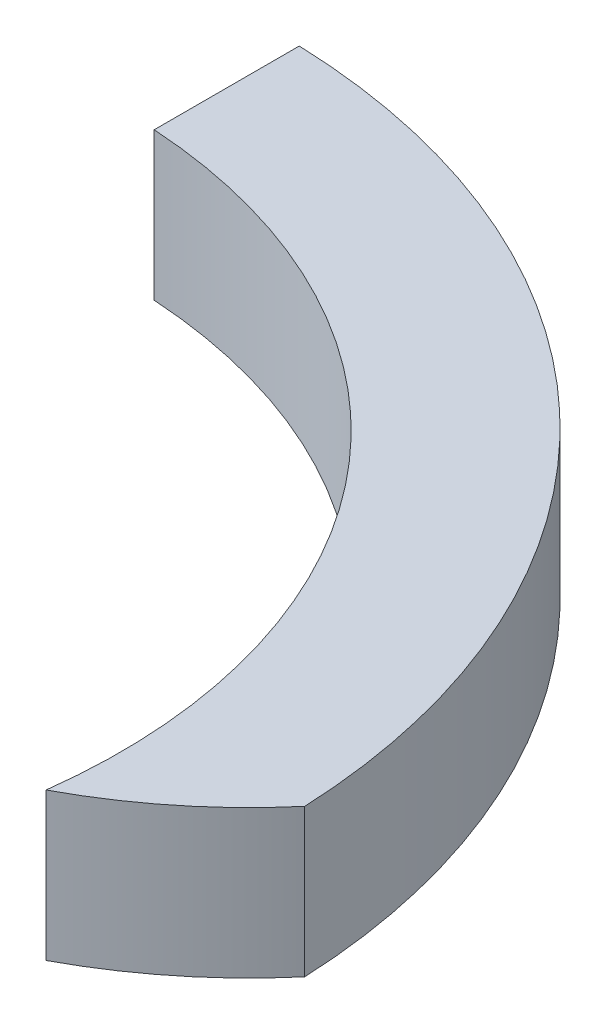
SolidWorks part; units mm, degrees
ref_plane "Front Plane" through (0, 0, 0) normal (0, 0, 1) x (1, 0, 0)
ref_plane "Top Plane" through (0, 0, 0) normal (0, 1, 0) x (1, 0, 0)
ref_plane "Right Plane" through (0, 0, 0) normal (1, 0, 0) x (0, 0, -1)
sketch "Sketch1" plane through (0, 0, 0) normal (0, 1, 0) x (1, 0, 0)
  line L0 (29, 109.5) -> (145, 109.5) construction
  line L1 (0, 0) -> (0, 116.767) construction
  line L2 (23.0118, 80.0276) -> (150.0261, 80.0276) construction
  line L3 (0, 80.0276) -> (0, 219.0676)
  line L4 (0, 219.0676) -> (103.0401, 219.0676)
  line L5 (103.0401, 219.0676) -> (103.0401, 195.9995)
  line L6 (103.0401, 195.9995) -> (23.0118, 195.9995)
  line L7 (23.0118, 195.9995) -> (23.0118, 161.0132)
  line L8 (150.0261, 80.0276) -> (150.0261, 148.0117)
  line L9 (150.0261, 148.0117) -> (172.9743, 148.0117)
  line L10 (172.9743, 80.0276) -> (172.9743, 148.0117)
  line L11 (172.9743, 80.0276) -> (175.6962, 80.0276) construction
  line L12 (103.0401, 219.0676) -> (173.9279, 219.0676) construction
  line L13 (23.0118, 136.0582) -> (23.0118, 80.0276)
  line L14 (173.9279, 219.0676) -> (173.9279, 172.1301) construction
  line L16 (173.9279, 172.1301) -> (150.0261, 172.1301)
  line L17 (173.9279, 172.1301) -> (173.9279, 219.0676)
  line L18 (173.9279, 219.0676) -> (127.0177, 219.0676)
  line L19 (127.0177, 195.9995) -> (127.0177, 219.0676)
  line L22 (127.0177, 195.9995) -> (150.0261, 195.9995)
  line L23 (150.0261, 172.1301) -> (150.0261, 195.9995)
  arc A0 (0, 80.0276) -> (172.9743, 80.0276) centre (86.4872, 86.7884) ccw
  arc A1 (23.0118, 80.0276) -> (112.0664, 28.4105) centre (86.519, 86.9649) ccw
  arc A2 (23.0118, 161.0132) -> (136.7449, 48.2112) centre (18.9852, 43.2164) cw
  arc A3 (23.0118, 136.0582) -> (112.0664, 28.4105) centre (17.0299, 40.4491) cw
  arc A4 (136.7449, 48.2112) -> (150.0261, 80.0276) centre (101.1223, 81.7615) ccw
extrude "Boss-Extrude1" add sketch "Sketch1" along normal blind 25.4
sketch "Sketch2" plane through (0, 25.4, 0) normal (0, 1, 0) x (1, 0, 0)
  line L1 (173.9279, 172.1301) -> (127.0177, 172.1301)
  line L2 (173.9279, 172.1301) -> (173.9279, 219.0676)
  line L3 (173.9279, 219.0676) -> (127.0177, 219.0676)
  line L4 (127.0177, 172.1301) -> (127.0177, 219.0676)
extrude "Cut-Extrude1" cut sketch "Sketch2" against normal through all both and the other way through all
sketch "Sketch3" plane through (0, 25.4, 0) normal (0, 1, 0) x (1, 0, 0)
  line L0 (23.0118, 161.0132) -> (23.0118, 136.0582)
  line L8 (172.9743, 80.0276) -> (172.9743, 148.0117)
  line L9 (172.9743, 148.0117) -> (150.0261, 148.0117)
  line L10 (150.0261, 148.0117) -> (150.0261, 80.0276)
  line L11 (23.0118, 161.0132) -> (23.0118, 195.9995)
  line L12 (23.0118, 195.9995) -> (103.0401, 195.9995)
  line L13 (103.0401, 195.9995) -> (103.0401, 219.0676)
  line L14 (103.0401, 219.0676) -> (0, 219.0676)
  line L15 (0, 219.0676) -> (0, 80.0276)
  arc A0 (23.0118, 136.0582) -> (112.0664, 28.4105) centre (17.0299, 40.4491) cw
  arc A1 (112.0664, 28.4105) -> (136.7449, 48.2112) centre (72.7035, 102.7496) ccw
  arc A3 (0, 80.0276) -> (172.9743, 80.0276) centre (86.4872, 86.7884) ccw
  arc A4 (136.7449, 48.2112) -> (150.0261, 80.0276) centre (101.1223, 81.7615) ccw
  arc A5 (136.7449, 48.2112) -> (23.0118, 161.0132) centre (18.9852, 43.2164) ccw
  arc A8 (136.7449, 48.2112) -> (23.0118, 161.0132) centre (18.9852, 43.2164) ccw
  dimension "D1" = 0
extrude "Cut-Extrude2" cut sketch "Sketch3" against normal through all both and the other way through all flip side to cut
